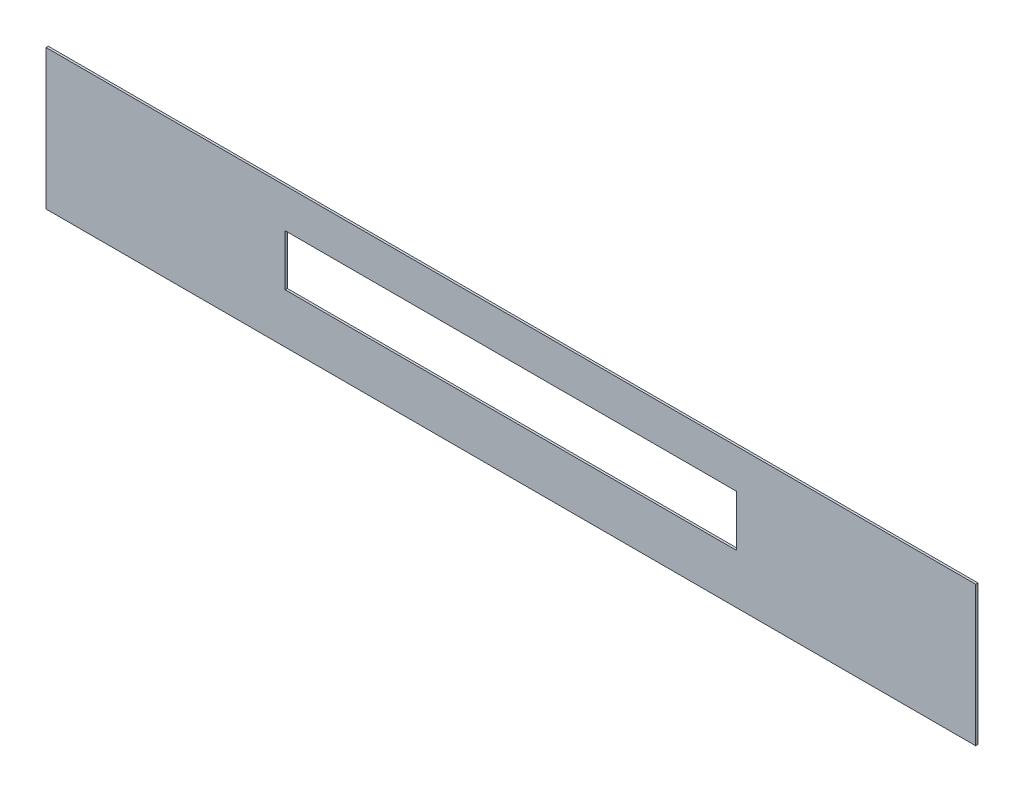
SolidWorks part; units mm, degrees
ref_plane "Front Plane" through (0, 0, 0) normal (0, 0, 1) x (1, 0, 0)
ref_plane "Top Plane" through (0, 0, 0) normal (0, 1, 0) x (1, 0, 0)
ref_plane "Right Plane" through (0, 0, 0) normal (1, 0, 0) x (0, 0, -1)
other "Configuration Table"
sketch "Sketch1" plane through (0, 0, 0) normal (0, 0, 1) x (1, 0, 0)
  line L1 (0, 0) -> (618, 0)
  line L2 (0, 0) -> (0, 93)
  line L3 (0, 93) -> (618, 93)
  line L4 (618, 0) -> (618, 93)
extrude "CEK_taze_on_dis_sac_1.5_1" add sketch "Sketch1" along normal blind 1.5 from offset 38.5 separate body
sketch "Sketch2" plane through (0, 0, 0) normal (0, 0, 1) x (1, 0, 0)
  line L1 (159, 33) -> (459, 33)
  line L2 (159, 33) -> (159, 67)
  line L3 (159, 67) -> (459, 67)
  line L4 (459, 33) -> (459, 67)
extrude "CEK_taze_on_dis_sac_1.5_2" cut sketch "Sketch2" along normal blind 14 from offset 27
